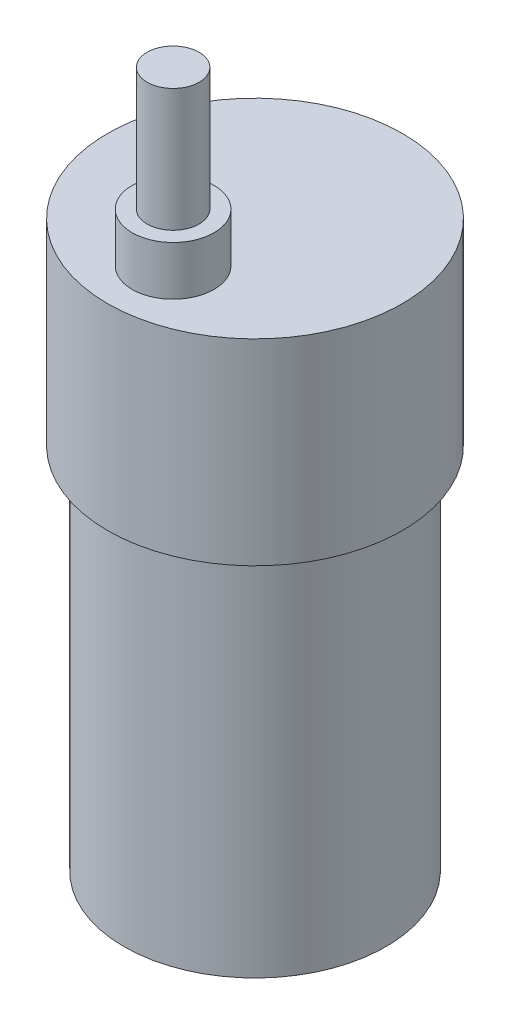
SolidWorks part; units mm, degrees
ref_plane "Front Plane" through (0, 0, 0) normal (0, 0, 1) x (1, 0, 0)
ref_plane "Top Plane" through (0, 0, 0) normal (0, 1, 0) x (1, 0, 0)
ref_plane "Right Plane" through (0, 0, 0) normal (1, 0, 0) x (0, 0, -1)
sketch "Sketch2" plane through (0, 0, 0) normal (0, 1, 0) x (1, 0, 0)
  circle A0 centre (0, 0) radius 16
  dimension "D1" = 32
extrude "Boss-Extrude1" add sketch "Sketch2" along normal blind 45
sketch "Sketch3" plane through (0, 45, 0) normal (0, 1, 0) x (1, 0, 0)
  circle A0 centre (0, 0) radius 18
  dimension "D1" = 36
extrude "Boss-Extrude2" add sketch "Sketch3" along normal blind 24
sketch "Sketch4" plane through (0, 69, 0) normal (0, 1, 0) x (1, 0, 0)
  circle A0 centre (0, -10) radius 5
  circle A1 centre (0, 0) radius 18 construction
  circle A2 centre (0, -10) radius 3.175
  dimension "D2" = 10
  dimension "D1" = 10
extrude "Boss-Extrude3" add sketch "Sketch4" along normal blind 6
sketch "Sketch5" plane through (0, 75, 0) normal (0, 1, 0) x (1, 0, 0)
  circle A0 centre (0, -10) radius 3.175
extrude "Boss-Extrude4" add sketch "Sketch5" along normal blind 15 and the other way blind 13.62
